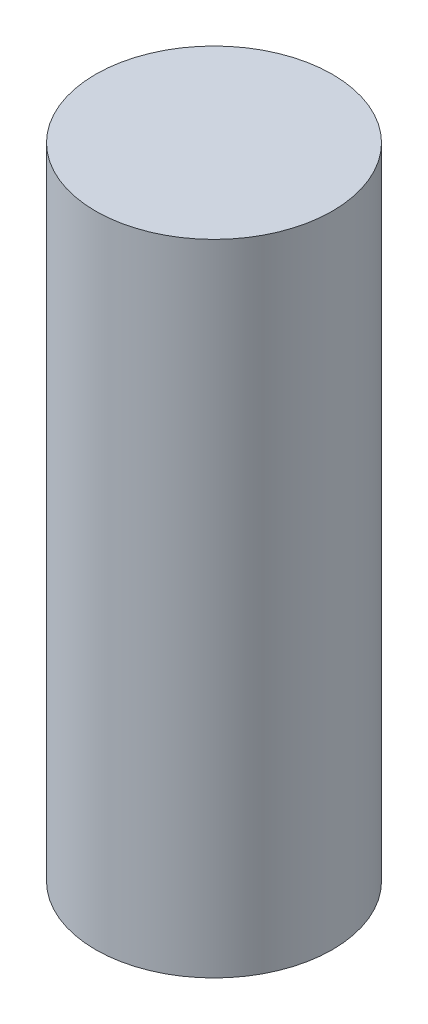
SolidWorks part; units mm, degrees
material "山毛榉"
ref_plane "前视基准面" through (0, 0, 0) normal (0, 0, 1) x (1, 0, 0)
ref_plane "上视基准面" through (0, 0, 0) normal (0, 1, 0) x (1, 0, 0)
ref_plane "右视基准面" through (0, 0, 0) normal (1, 0, 0) x (0, 0, -1)
sketch "草图1" plane through (0, 0, 0) normal (0, 1, 0) x (1, 0, 0)
  circle A0 centre (66.4072, -51.1464) radius 10
extrude "凸台-拉伸1" add sketch "草图1" along normal blind 54
